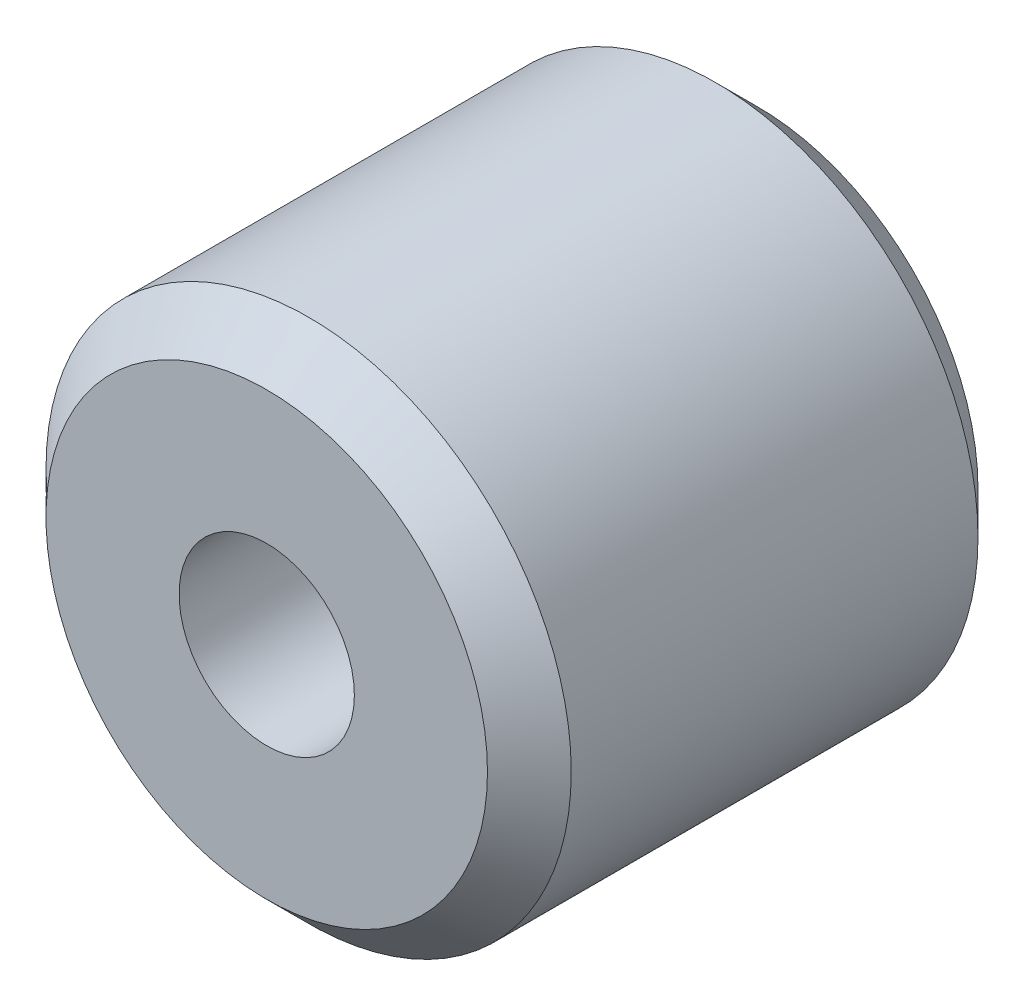
SolidWorks part; units mm, degrees
ref_plane "Front Plane" through (0, 0, 0) normal (0, 0, 1) x (1, 0, 0)
ref_plane "Top Plane" through (0, 0, 0) normal (0, 1, 0) x (1, 0, 0)
ref_plane "Right Plane" through (0, 0, 0) normal (1, 0, 0) x (0, 0, -1)
sketch "Sketch1" plane through (0, 0, 0) normal (0, 0, 1) x (1, 0, 0)
  circle A0 centre (0, 0) radius 1.59
  circle A1 centre (0, 0) radius 4.765
  dimension "D1" = 9.53
  dimension "D2" = 3.18
extrude "Boss-Extrude1" add sketch "Sketch1" along normal mid plane 8.9
chamfer "Chamfer1" distance 0.76 angle 45 2 edges at (4.765, 0, -4.45) (4.765, 0, 4.45)
